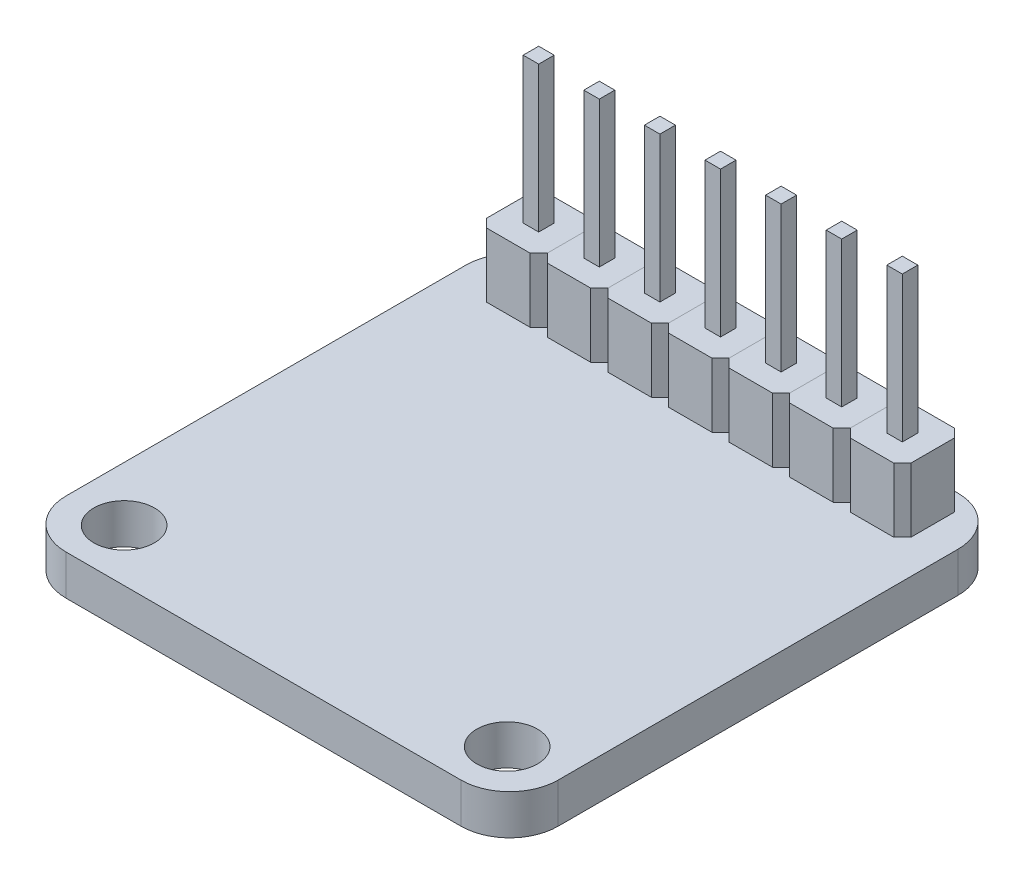
SolidWorks part; units mm, degrees
ref_plane "Front Plane" through (0, 0, 0) normal (0, 0, 1) x (1, 0, 0)
ref_plane "Top Plane" through (0, 0, 0) normal (0, 1, 0) x (1, 0, 0)
ref_plane "Right Plane" through (0, 0, 0) normal (1, 0, 0) x (0, 0, -1)
sketch "Sketch1" plane through (0, 0, 0) normal (0, 1, 0) x (1, 0, 0)
  line L1 (-10.15, 10.25) -> (10.15, 10.25)
  line L2 (-10.15, 10.25) -> (-10.15, -10.25)
  line L3 (-10.15, -10.25) -> (10.15, -10.25)
  line L4 (10.15, 10.25) -> (10.15, -10.25)
  line L5 (-10.15, 10.25) -> (10.15, -10.25) construction
  line L6 (-10.15, -10.25) -> (10.15, 10.25) construction
  point P0 (0, 0)
  dimension "D1" = 20.3
  dimension "D2" = 20.5
extrude "Boss-Extrude1" add sketch "Sketch1" along normal blind 1.65
fillet "Fillet1" radius 2 4 edges at (10.15, 0.825, -10.25) (-10.15, 0.825, -10.25) (-10.15, 0.825, 10.25) (10.15, 0.825, 10.25)
sketch "Sketch2" plane through (0, 1.65, 0) normal (0, 1, 0) x (1, 0, 0)
  line L0 (-7.9, -8.1) -> (7.9, -8.1) construction
  line L1 (-8.15, -10.25) -> (8.15, -10.25) construction
  line L2 (-10.15, 8.25) -> (-10.15, -8.25) construction
  circle A0 centre (7.9, -8.1) radius 1.25
  circle A1 centre (-7.9, -8.1) radius 1.25
  point P4 (0, -8.1)
  point P7 (0, -10.25)
  dimension "D1" = 2.5
  dimension "D2" = 2.25
  dimension "D3" = 2.15
extrude "Cut-Extrude1" cut sketch "Sketch2" against normal through all
sketch "Sketch3" plane through (0, 1.65, 0) normal (0, 1, 0) x (1, 0, 0)
  line L0 (-8.395, 9.85) -> (-6.6021, 9.85)
  line L4 (-6.6021, 9.85) -> (-6.2486, 9.4964)
  line L10 (-8.395, 9.85) -> (-8.7486, 9.4964)
  line L11 (-8.395, 7.35) -> (-8.7486, 7.7036)
  line L12 (-8.7486, 7.7036) -> (-8.7486, 9.4964)
  line L16 (-6.2486, 9.4964) -> (-6.2486, 7.7036)
  line L17 (-10.15, 8.25) -> (-10.15, -8.25) construction
  line L18 (8.15, 10.25) -> (-8.15, 10.25) construction
  line L27 (-6.6022, 7.35) -> (-6.2486, 7.7036)
  line L31 (-8.395, 7.35) -> (-6.6022, 7.35)
  dimension "D1" = 2.5
  dimension "D2" = 2.5
  dimension "D3" = 0.4
  dimension "D4" = 0.245
  dimension "D5" = 135
  dimension "D6" = 0.5
extrude "Boss-Extrude2" add sketch "Sketch3" along normal blind 2.65
sketch "Sketch4" plane through (0, 4.3, 0) normal (0, 1, 0) x (1, 0, 0)
  line L0 (-8.7486, 9.4964) -> (-8.7486, 7.7036) construction
  line L1 (-7.8186, 8.92) -> (-7.1786, 8.92)
  line L2 (-7.8186, 8.92) -> (-7.8186, 8.28)
  line L3 (-7.8186, 8.28) -> (-7.1786, 8.28)
  line L4 (-7.1786, 8.92) -> (-7.1786, 8.28)
  line L5 (-7.8186, 8.92) -> (-7.1786, 8.28) construction
  line L6 (-7.8186, 8.28) -> (-7.1786, 8.92) construction
  line L7 (-6.6021, 9.85) -> (-8.395, 9.85) construction
  point P0 (-7.4986, 8.6)
  point P9 (-8.7486, 8.6)
  point P13 (-7.4986, 9.85)
  dimension "D1" = 0.64
extrude "Boss-Extrude3" add sketch "Sketch4" along normal blind 6
pattern_linear "LPattern1" count 7 spacing 2.5 along (1, 0, 0) of "Boss-Extrude2", "Boss-Extrude3"
sketch "Sketch5" plane through (0, 0, 0) normal (0, -1, 0) x (1, 0, 0)
  line L1 (-8.75, -6.5) -> (8.75, -6.5)
  line L2 (-8.75, -6.5) -> (-8.75, 4.5)
  line L3 (-8.75, 4.5) -> (8.75, 4.5)
  line L4 (8.75, -6.5) -> (8.75, 4.5)
  line L5 (8.15, -10.25) -> (-8.15, -10.25) construction
  point P4 (-9.1595, -7.2689)
  point P5 (0, -10.25)
  point P9 (0, -6.5)
  dimension "D1" = 17.5
  dimension "D2" = 11
  dimension "D3" = 4.5
extrude "Boss-Extrude4" add sketch "Sketch5" along normal blind 1.35
